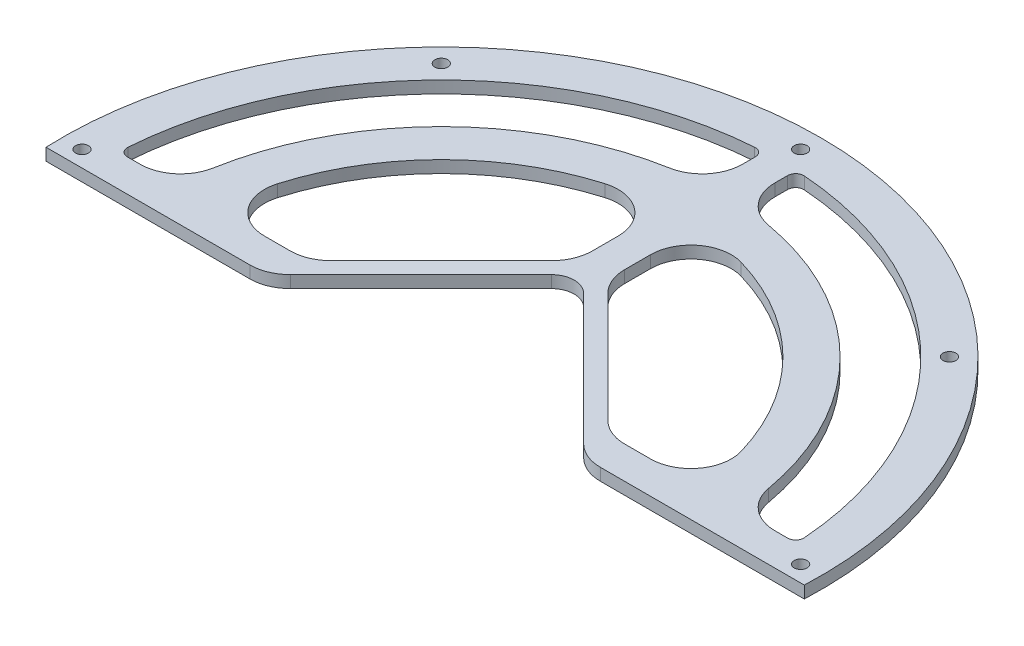
SolidWorks part; units mm, degrees
ref_plane "前视基准面" through (0, 0, 0) normal (0, 0, 1) x (1, 0, 0)
ref_plane "上视基准面" through (0, 0, 0) normal (0, 1, 0) x (1, 0, 0)
ref_plane "右视基准面" through (0, 0, 0) normal (1, 0, 0) x (0, 0, -1)
other "Configuration Table"
sketch "草图1" plane through (0, 0, 0) normal (0, 1, 0) x (1, 0, 0)
  line L9 (-31.221, 4) -> (-36.292, -1.0711)
  line L12 (31.221, 4) -> (36.292, -1.0711)
  line L15 (46.95, 4) -> (46.95, -4) construction
  line L16 (46.95, 4) -> (47.7604, 4)
  line L17 (46.95, -4) -> (83.8046, -4)
  line L18 (46.95, 4) -> (41.3631, 4)
  line L19 (46.95, -4) -> (43.3631, -4)
  line L20 (-46.95, -4) -> (-43.3631, -4)
  line L21 (-46.95, 4) -> (-41.3631, 4)
  line L22 (-46.95, 4) -> (-47.7604, 4)
  line L23 (-46.95, -4) -> (-83.8046, -4)
  line L24 (-78.5319, 4) -> (-81.6799, 4)
  line L25 (83.8046, -4) -> (93.8148, -4)
  line L26 (-4, 78.5319) -> (-4, 81.6799)
  line L27 (-83.8046, -4) -> (-93.8148, -4)
  line L28 (-4, 46.95) -> (-4, 41.3631)
  line L29 (4, 46.95) -> (4, 41.3631)
  line L30 (-4, 46.95) -> (-4, 47.7604)
  line L31 (4, 46.95) -> (4, 47.7604)
  line L32 (4, 78.5319) -> (4, 81.6799)
  line L33 (-31.221, 4) -> (-4, 31.221)
  line L34 (78.5319, 4) -> (81.6799, 4)
  line L35 (4, 83.8046) -> (4, 88.81) [skipped]
  line L36 (31.221, 4) -> (4, 31.221)
  line L38 (-34.292, 6.9289) -> (-6.9289, 34.292)
  line L40 (34.292, 6.9289) -> (6.9289, 34.292)
  line L48 (35.221, 0) -> (93.9, 0) construction
  arc A2 (64.6464, -4) -> (-64.6464, -4) centre (0, 0) ccw construction
  arc A3 (88.81, -4) -> (-88.81, -4) centre (0, 0) ccw construction
  arc A7 (93.8148, -4) -> (-93.8148, -4) centre (0, 0) ccw
  arc A21 (57.3566, 16.8129) -> (16.8129, 57.3566) centre (0, 0) ccw
  arc A22 (68.6871, 12.245) -> (12.245, 68.6871) centre (0, 0) ccw
  arc A23 (83.6745, 6.1465) -> (6.1465, 83.6745) centre (0, 0) ccw
  arc A24 (-6.1465, 83.6745) -> (-83.6745, 6.1465) centre (0, 0) ccw
  arc A25 (-12.245, 68.6871) -> (-68.6871, 12.245) centre (0, 0) ccw
  arc A26 (-16.8129, 57.3566) -> (-57.3566, 16.8129) centre (0, 0) ccw
  circle A28 centre (88.9, 0) radius 1.6
  circle A32 centre (-88.9, 0) radius 1.6
  circle A33 centre (-62.8618, 62.8618) radius 1.6
  circle A34 centre (0, 88.9) radius 1.6
  circle A35 centre (62.8618, 62.8618) radius 1.6
  arc A50 (34.292, 6.9289) -> (41.3631, 4) centre (41.3631, 14) ccw
  arc A51 (36.292, -1.0711) -> (43.3631, -4) centre (43.3631, 6) ccw
  arc A52 (-36.292, -1.0711) -> (-43.3631, -4) centre (-43.3631, 6) cw
  arc A53 (-34.292, 6.9289) -> (-41.3631, 4) centre (-41.3631, 14) cw
  arc A54 (-4, 31.221) -> (4, 31.221) centre (0, 27.221) cw
  arc A55 (6.9289, 34.292) -> (4, 41.3631) centre (14, 41.3631) cw
  arc A56 (-4, 41.3631) -> (-6.9289, 34.292) centre (-14, 41.3631) cw
  arc A57 (-4, 78.5319) -> (-12.245, 68.6871) centre (-14, 78.5319) cw
  arc A58 (-68.6871, 12.245) -> (-78.5319, 4) centre (-78.5319, 14) cw
  arc A59 (12.245, 68.6871) -> (4, 78.5319) centre (14, 78.5319) cw
  arc A60 (78.5319, 4) -> (68.6871, 12.245) centre (78.5319, 14) cw
  arc A61 (-4, 81.6799) -> (-6.1465, 83.6745) centre (-6, 81.6799) ccw
  arc A62 (-83.6745, 6.1465) -> (-81.6799, 4) centre (-81.6799, 6) ccw
  arc A63 (6.1465, 83.6745) -> (4, 81.6799) centre (6, 81.6799) ccw
  arc A64 (83.6745, 6.1465) -> (81.6799, 4) centre (81.6799, 6) cw
  arc A65 (16.8129, 57.3566) -> (4, 47.7604) centre (14, 47.7604) ccw
  arc A66 (-4, 47.7604) -> (-16.8129, 57.3566) centre (-14, 47.7604) ccw
  arc A67 (57.3566, 16.8129) -> (47.7604, 4) centre (47.7604, 14) cw
  arc A68 (-47.7604, 4) -> (-57.3566, 16.8129) centre (-47.7604, 14) cw
  point P16 (0, 8)
  point P20 (37.221, 4)
  point P29 (-37.221, 4)
  point P31 (0, -8)
  point P38 (-8, 0)
  point P41 (-4, 69.6552)
  point P44 (46.95, 0)
  point P45 (-69.6552, 4)
  point P47 (46.95, 4)
  point P50 (46.95, -4)
  point P56 (4, 69.6552)
  point P68 (69.6552, 4)
  dimension "D2" = 10
  dimension "D3" = 6
  dimension "D4" = 6
  dimension "D5" = 3.2
  dimension "D6" = 10
  dimension "D7" = 10
  dimension "D8" = 10
  dimension "D9" = 2
  dimension "D12" = 2
  dimension "D13" = 2
  dimension "D14" = 10
  dimension "D10" = 2
  dimension "D11" = 2
extrude "凸台-拉伸1" add sketch "草图1" along normal blind 3
